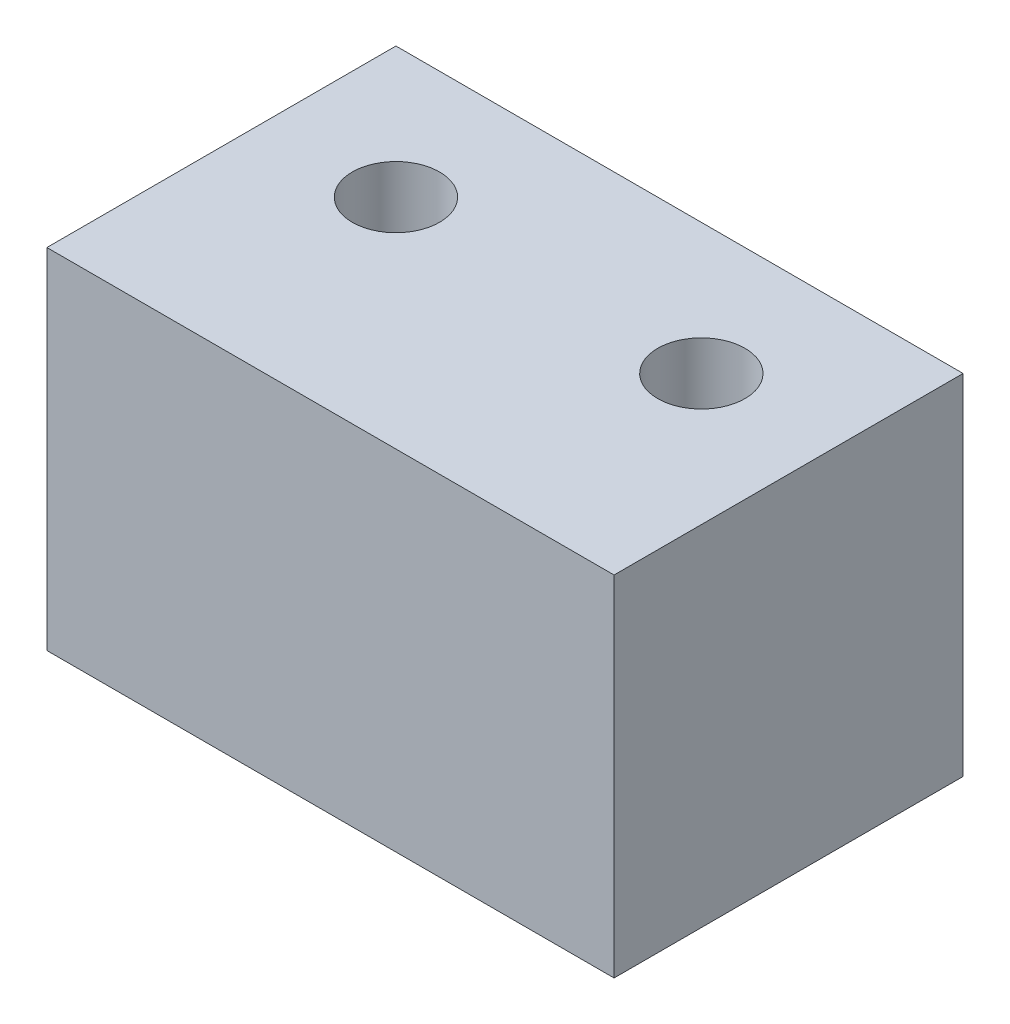
SolidWorks part; units mm, degrees
ref_plane "Front" through (0, 0, 0) normal (0, 0, 1) x (1, 0, 0)
ref_plane "Top" through (0, 0, 0) normal (0, 1, 0) x (1, 0, 0)
ref_plane "Right" through (0, 0, 0) normal (1, 0, 0) x (0, 0, -1)
sketch "Sketch1" plane through (0, 0, 0) normal (0, 1, 0) x (1, 0, 0)
  line L1 (-41.275, -25.4) -> (41.275, -25.4)
  line L2 (-41.275, -25.4) -> (-41.275, 25.4)
  line L3 (-41.275, 25.4) -> (41.275, 25.4)
  line L4 (41.275, -25.4) -> (41.275, 25.4)
  line L5 (-41.275, -25.4) -> (41.275, 25.4) construction
  line L6 (-41.275, 25.4) -> (41.275, -25.4) construction
  point P0 (0, 0)
  dimension "D1" = 82.55
  dimension "D2" = 50.8
extrude "Boss-Extrude1" add sketch "Sketch1" along normal mid plane 50.8 contours L3 L4 L1 L2
sketch "Sketch2" plane through (0, 25.4, 0) normal (0, 1, 0) x (1, 0, 0)
  line L0 (22.225, 6.35) -> (-22.225, 6.35) construction
  line L1 (0, -50) -> (0, 50) construction
  line L2 (-50, 0) -> (50, 0) construction
  point P0 (22.225, 6.35)
  point P1 (-22.225, 6.35)
  point P4 (0, 6.35)
  dimension "D1" = 44.45
  dimension "D2" = 6.35
hole_wizard "1/2 (0.5000) Dowel Hole1" positions "Sketch3" profile "Sketch5" hole size "1/2" standard "ANSI Inch" end condition through all
sketch "Sketch3" plane through (0, 25.4, 0) normal (0, 1, 0) x (1, 0, 0)
  point P0 (22.225, 6.35)
  point P3 (-22.225, 6.35)
sketch "Sketch5" plane through (22.225, 25.4, -6.35) normal (1, 0, 0) x (0, 0, 1)
  line L0 (0, 0) -> (0, 50.8)
  line L1 (0, 50.8) -> (6.35, 50.8)
  line L2 (6.35, 50.8) -> (6.35, 0)
  line L5 (6.35, 0) -> (0, 0)
  line L11 (0, -6.35) -> (0, 107.95) construction
  dimension "Thru Hole Dia." = 12.7
  dimension "Thru Hole Depth" = 50.8
sketch "Sketch6" plane through (-41.275, 0, 0) normal (-1, 0, 0) x (0, 0, 1)
  line L0 (0, 12.7) -> (0, -12.7) construction
  line L1 (50, 0) -> (-50, 0) construction
  line L2 (0, -50) -> (0, 50) construction
  point P0 (0, 12.7)
  point P1 (0, -12.7)
  point P4 (0, 0)
  dimension "D1" = 25.4
hole_wizard "1/4-20 Tapped Hole1" positions "Sketch7" profile "Sketch9" tap size "1/4-20" standard "ANSI Inch"
sketch "Sketch7" plane through (-41.275, 0, 0) normal (-1, 0, 0) x (0, 0, 1)
  point P0 (0, 12.7)
  point P3 (0, -12.7)
sketch "Sketch9" plane through (-41.275, 12.7, 0) normal (0, 1, 0) x (0, 0, 1)
  line L0 (0, 0) -> (0, 14.2338)
  line L1 (0, 14.2338) -> (2.5527, 12.7)
  line L2 (2.5527, 12.7) -> (2.5527, 0)
  line L5 (2.5527, 0) -> (0, 0)
  line L10 (0, 14.2338) -> (-2.5527, 12.7) construction
  line L11 (0, -6.35) -> (0, 107.95) construction
  dimension "Tap Drill Dia." = 5.1054
  dimension "Tap Drill Depth" = 12.7
  dimension "Drill Angle" = 118
cosmetic thread "Hole Thread1" parameters "D1"=12.7, "D2"=6.35
cosmetic thread "Hole Thread2" parameters "D1"=12.7, "D2"=6.35
